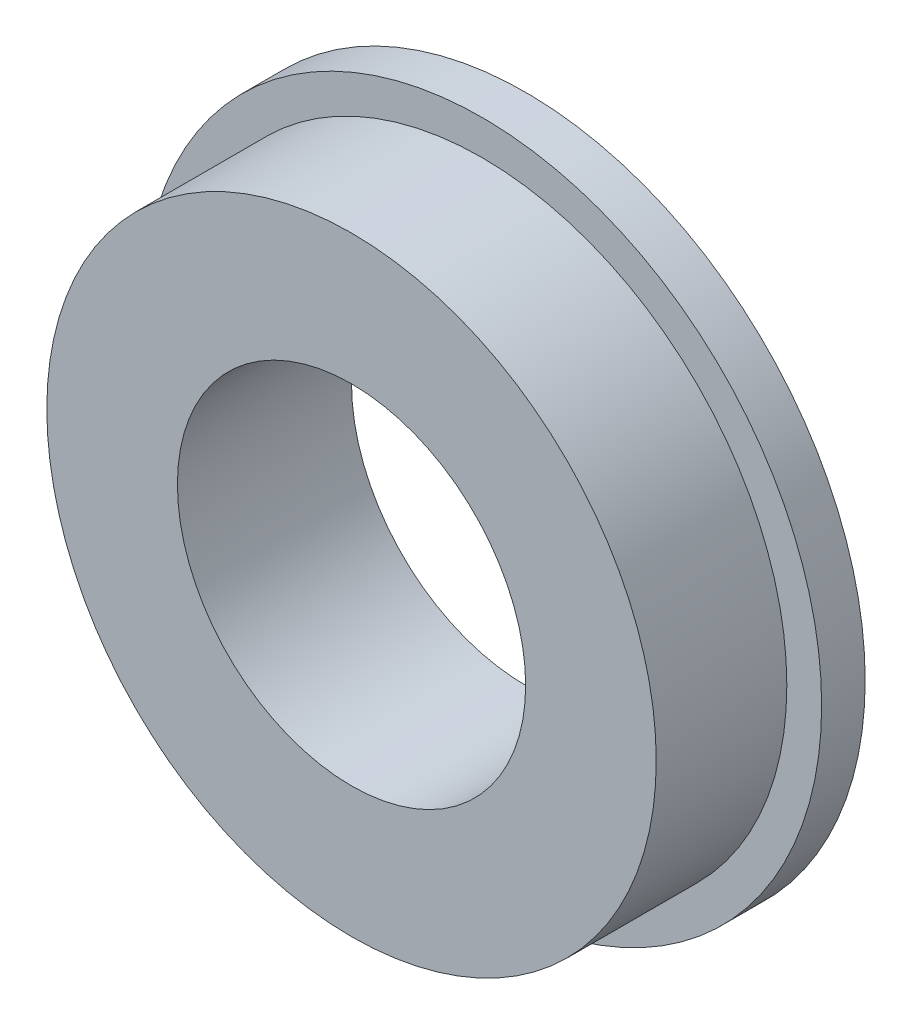
SolidWorks part; units mm, degrees
ref_plane "前视基准面" through (0, 0, 0) normal (0, 0, 1) x (1, 0, 0)
ref_plane "上视基准面" through (0, 0, 0) normal (0, 1, 0) x (1, 0, 0)
ref_plane "右视基准面" through (0, 0, 0) normal (1, 0, 0) x (0, 0, -1)
sketch "草图1" plane through (0, 0, 0) normal (0, 0, 1) x (1, 0, 0)
  circle A0 centre (0, 0) radius 7.8
  dimension "D1" = 15.6
extrude "凸台-拉伸1" add sketch "草图1" along normal blind 1
sketch "草图2" plane through (0, 0, 1) normal (0, 0, 1) x (1, 0, 0)
  circle A0 centre (0, 0) radius 7
extrude "凸台-拉伸2" add sketch "草图2" along normal blind 3
sketch "草图3" plane through (0, 0, 0) normal (0, 0, -1) x (-1, 0, 0)
  circle A0 centre (0, 0) radius 4
extrude "切除-拉伸1" cut sketch "草图3" against normal blind 5
